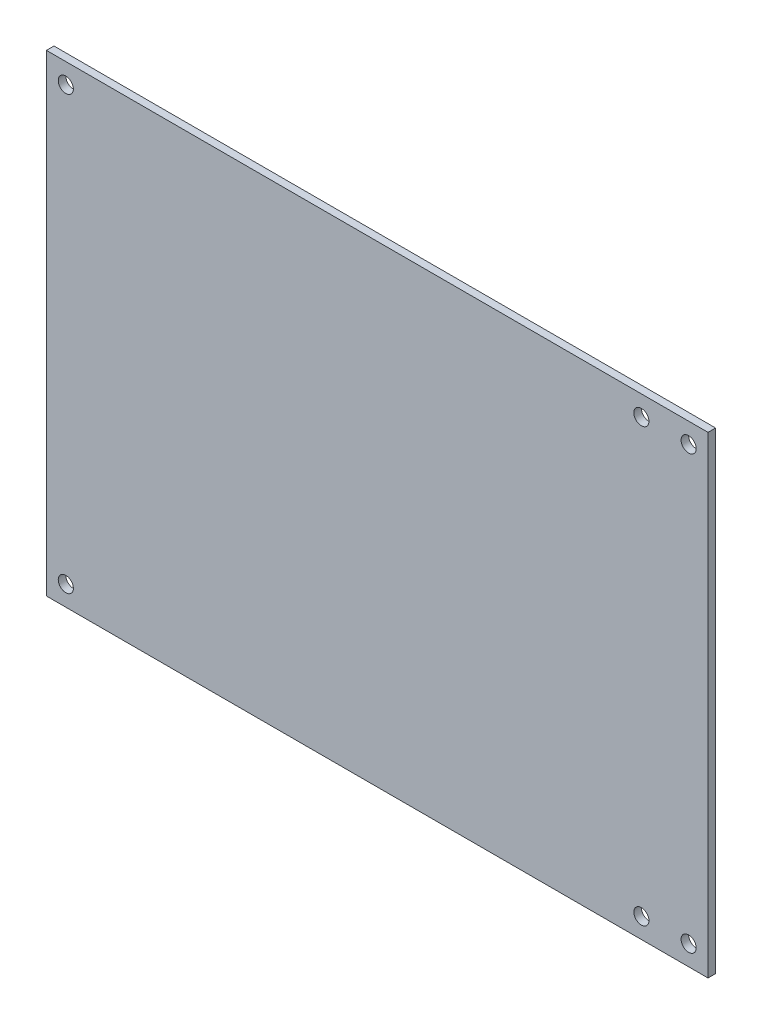
SolidWorks part; units mm, degrees
ref_plane "Спереди" through (0, 0, 0) normal (0, 0, 1) x (1, 0, 0)
ref_plane "Сверху" through (0, 0, 0) normal (0, 1, 0) x (1, 0, 0)
ref_plane "Справа" through (0, 0, 0) normal (1, 0, 0) x (0, 0, -1)
sketch "Эскиз1" plane through (0, 0, 0) normal (0, 0, 1) x (1, 0, 0)
  line L1 (-70, 50) -> (70, 50)
  line L2 (-70, 50) -> (-70, -50)
  line L3 (-70, -50) -> (70, -50)
  line L4 (70, 50) -> (70, -50)
  line L5 (-70, 50) -> (70, -50) construction
  line L6 (-70, -50) -> (70, 50) construction
  point P0 (0, 0)
  dimension "D1" = 140
  dimension "D2" = 100
extrude "Бобышка-Вытянуть1" add sketch "Эскиз1" along normal blind 1.6
sketch "Эскиз2" plane through (0, 0, 1.6) normal (0, 0, 1) x (1, 0, 0)
  line L0 (0, 65.1001) -> (0, -79.8341) construction
  line L1 (-94.9267, 0) -> (96.3112, 0) construction
  circle A0 centre (-65.9, 45.75) radius 1.6
  circle A1 centre (65.9, 45.75) radius 1.6
  circle A2 centre (65.9, -45.75) radius 1.6
  circle A3 centre (-65.9, -45.75) radius 1.6
  circle A4 centre (55.9, 45.75) radius 1.6
  circle A5 centre (55.9, -45.75) radius 1.6
  dimension "D1" = 3.2
  dimension "D2" = 131.8
  dimension "D3" = 91.5
  dimension "D4" = 2
extrude "Вырез-Вытянуть1" cut sketch "Эскиз2" against normal through all
